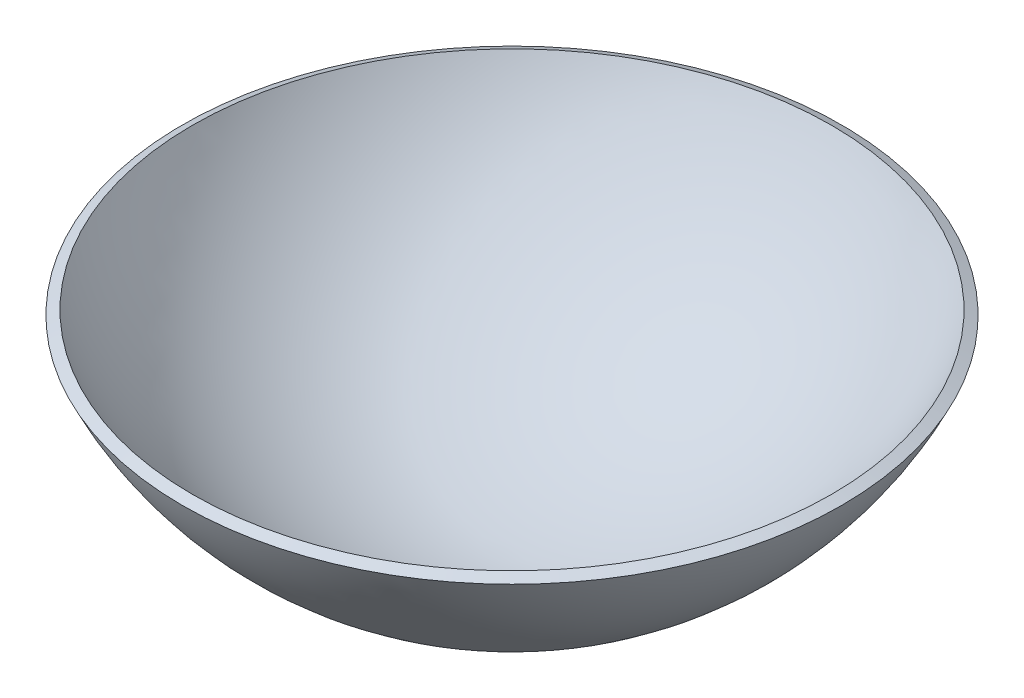
SolidWorks part; units mm, degrees
ref_plane "Front Plane" through (0, 0, 0) normal (0, 0, 1) x (1, 0, 0)
ref_plane "Top Plane" through (0, 0, 0) normal (0, 1, 0) x (1, 0, 0)
ref_plane "Right Plane" through (0, 0, 0) normal (1, 0, 0) x (0, 0, -1)
sketch "Sketch1" plane through (0, 0, 0) normal (0, 0, 1) x (1, 0, 0)
  line L0 (0, -84.0774) -> (0, -81.5374)
  line L1 (73.898, -34.4592) -> (76.2, -35.5326)
  arc A0 (0, -84.0774) -> (76.2, -35.5326) centre (0, 0) ccw
  arc A1 (0, -81.5374) -> (73.898, -34.4592) centre (0, 0) ccw
  dimension "D1" = 65
  dimension "D2" = 76.2
  dimension "D3" = 2.54
ref_axis "Axis1" through (0, 83.82, 0) along (0, -1, 0)
revolve "Revolve6" add sketch "Sketch1" angle 360 about axis through (0, 83.82, 0) along (0, -1, 0)
